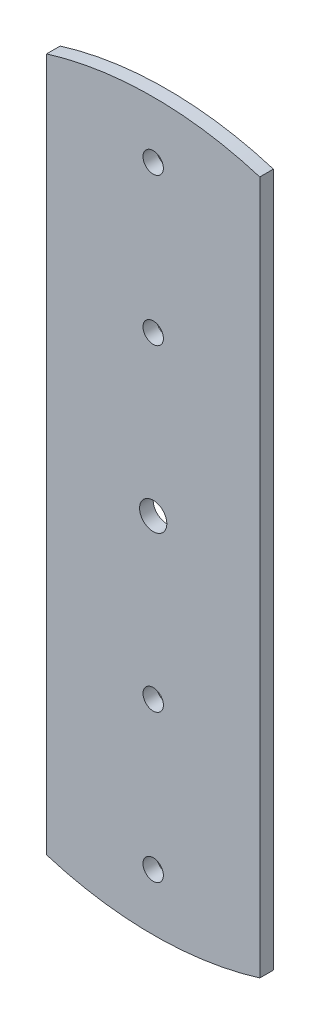
SolidWorks part; units mm, degrees
ref_plane "Płaszczyzna przednia" through (0, 0, 0) normal (0, 0, 1) x (1, 0, 0)
ref_plane "Płaszczyzna górna" through (0, 0, 0) normal (0, 1, 0) x (1, 0, 0)
ref_plane "Płaszczyzna prawa" through (0, 0, 0) normal (1, 0, 0) x (0, 0, -1)
sketch "Szkic1" plane through (0, 0, 0) normal (0, 0, 1) x (1, 0, 0)
  line L2 (-47, 152.9412) -> (-47, -152.9412)
  line L4 (47, 152.9412) -> (47, -152.9412)
  line L5 (-30.8442, 156.9988) -> (30.8442, -156.9988) construction
  line L6 (-30.8442, -156.9988) -> (30.8442, 156.9988) construction
  arc A0 (-47, -152.9412) -> (47, -152.9412) centre (0, 0) ccw
  circle A1 centre (0, 0) radius 6
  arc A2 (47, 152.9412) -> (-47, 152.9412) centre (0, 0) ccw
  circle A3 centre (0, -70) radius 4.5
  circle A4 centre (0, 70) radius 4.5
  circle A5 centre (0, 135) radius 4.5
  circle A6 centre (0, -135) radius 4.5
  dimension "D1" = 320
  dimension "D2" = 12
  dimension "D6" = 9
  dimension "D7" = 9
  dimension "D8" = 135
  dimension "D10" = 9
  dimension "D11" = 9
  dimension "D3" = 94
  dimension "D4" = 70
  dimension "D5" = 70
  dimension "D9" = 135
extrude "Dodanie-wyciągnięcie1" add sketch "Szkic1" along normal blind 6
